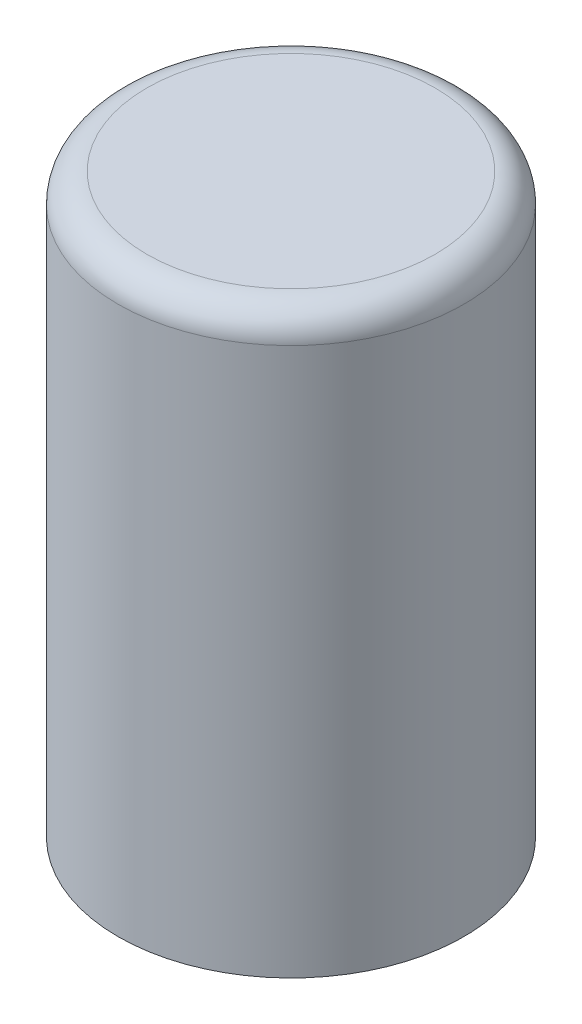
SolidWorks part; units mm, degrees
ref_plane "Front Plane" through (0, 0, 0) normal (0, 0, 1) x (1, 0, 0)
ref_plane "Top Plane" through (0, 0, 0) normal (0, 1, 0) x (1, 0, 0)
ref_plane "Right Plane" through (0, 0, 0) normal (1, 0, 0) x (0, 0, -1)
sketch "Sketch1" plane through (0, 0, 0) normal (0, 1, 0) x (1, 0, 0)
  circle A0 centre (0, 0) radius 3
  dimension "D1" = 6
extrude "Boss-Extrude1" add sketch "Sketch1" along normal blind 10
sketch "Sketch2" plane through (0, 0, 0) normal (0, -1, 0) x (1, 0, 0)
  line L0 (-1.5, 1) -> (1.5, 1)
  line L1 (-1.5, 1) -> (-1.5, -1)
  line L2 (1.5, 1) -> (1.5, -1)
  line L3 (-1.5, -1) -> (1.5, -1)
  line L4 (-1.5, -1) -> (1.5, 1) construction
  point P0 (0, 0)
  dimension "D1" = 3
  dimension "D2" = 2
extrude "Cut-Extrude1" cut sketch "Sketch2" along direction (0, 1, 0) on the side against the normal blind 7
chamfer "Chamfer1" distance 0.5 angle 45 2 edges at (0, 0, -1) (0, 0, 1)
fillet "Fillet1" radius 0.5 1 edges at (0, 10, 3)
